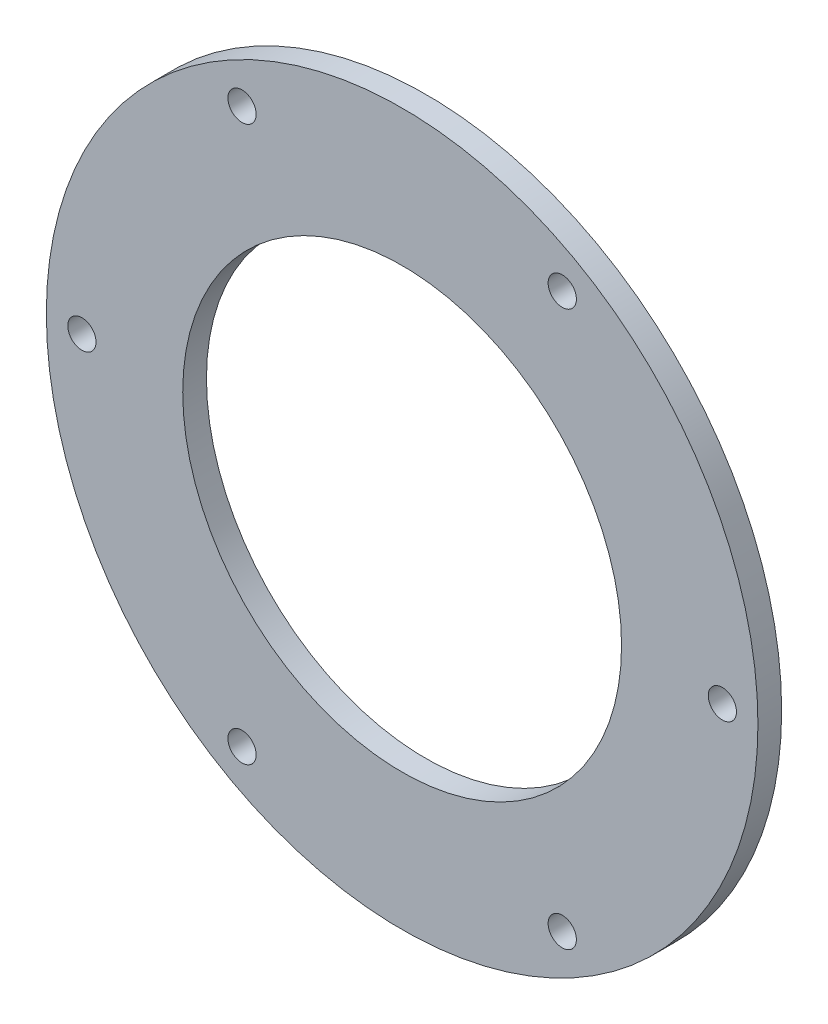
SolidWorks part; units mm, degrees
ref_plane "Front Plane" through (0, 0, 0) normal (0, 0, 1) x (1, 0, 0)
ref_plane "Top Plane" through (0, 0, 0) normal (0, 1, 0) x (1, 0, 0)
ref_plane "Right Plane" through (0, 0, 0) normal (1, 0, 0) x (0, 0, -1)
sketch "Sketch1" plane through (0, 0, 0) normal (0, 0, 1) x (1, 0, 0)
  circle A0 centre (0, 0) radius 60
  circle A1 centre (0, 0) radius 37
  point P20 (0, 0)
  point P23 (0, 0)
  dimension "D1" = 120
  dimension "D2" = 74
extrude "Boss-Extrude1" add sketch "Sketch1" along normal blind 4
hole_wizard "3/16 (0.1875) Dowel Hole1" positions "3DSketch2" profile "Sketch4" hole size "3/16" standard "ANSI Inch" end condition up to next
sketch3d "3DSketch2"
  line L0 (-39.5024, 68.4202, 4) -> (48.0499, -83.2249, 4) construction
  line L1 (-39.8539, -69.0291, 4) -> (39.8539, 69.0291, 4) construction
  line L2 (-71.0127, 0, 4) -> (88.1271, 0, 4) construction
  circle A0 centre (0, 0, 4) radius 54 construction
  point P0 (-54, 0, 4)
  point P2 (54, 0, 4)
  point P4 (-27, 46.7654, 4)
  point P6 (-27, -46.7654, 4)
  point P8 (27, 46.7654, 4)
  point P10 (27, -46.7654, 4)
  point P20 (0, 0, 58)
sketch "Sketch4" plane through (-54, 0, 4) normal (1, 0, 0) x (0, -1, 0)
  line L0 (0, 0) -> (0, 4)
  line L1 (0, 4) -> (2.3812, 4)
  line L2 (2.3812, 4) -> (2.3812, 0)
  line L5 (2.3812, 0) -> (0, 0)
  line L11 (0, -6.35) -> (0, 107.95) construction
  dimension "Thru Hole Dia." = 4.7625
  dimension "Thru Hole Depth" = 4
sketch "Sketch2" plane through (0, 0, 4) normal (0, 0, 1) x (1, 0, 0)
  line L0 (-71.0127, 0) -> (88.1271, 0) construction
  line L1 (-39.8539, -69.0291) -> (39.8539, 69.0291) construction
  line L2 (-39.5024, 68.4202) -> (48.0499, -83.2249) construction
  circle A0 centre (0, 0) radius 54
  dimension "D1" = 60
  dimension "D2" = 60
